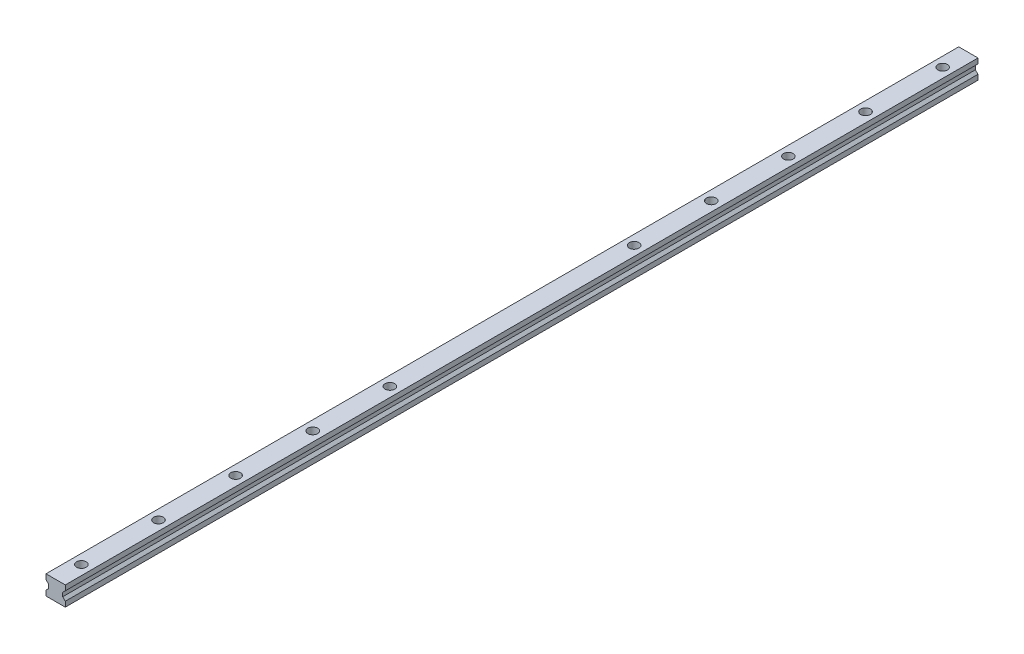
SolidWorks part; units mm, degrees
ref_plane "Front Plane" through (0, 0, 0) normal (0, 0, 1) x (1, 0, 0)
ref_plane "Top Plane" through (0, 0, 0) normal (0, 1, 0) x (1, 0, 0)
ref_plane "Right Plane" through (0, 0, 0) normal (1, 0, 0) x (0, 0, -1)
sketch "Sketch1" plane through (0, 0, 0) normal (0, 0, 1) x (1, 0, 0)
  line L0 (0, 17.31) -> (0, -6.39) construction
  line L1 (-7.5, 0) -> (7.5, 0)
  line L2 (7.5, 0) -> (7.5, 4)
  line L3 (7.5, 4) -> (5.5, 6)
  line L4 (5.5, 6) -> (5.5, 9)
  line L5 (5.5, 9) -> (7.5, 11)
  line L6 (7.5, 11) -> (7.5, 15)
  line L7 (7.5, 15) -> (-7.5, 15)
  line L8 (-7.5, 11) -> (-7.5, 15)
  line L9 (-5.5, 9) -> (-7.5, 11)
  line L10 (-5.5, 6) -> (-5.5, 9)
  line L11 (-7.5, 4) -> (-5.5, 6)
  line L12 (-7.5, 0) -> (-7.5, 4)
  point P11 (0, 15)
  point P17 (0, 0)
  dimension "D1" = 7.5
  dimension "D2" = 15
  dimension "D3" = 4
  dimension "D4" = 4
  dimension "D5" = 45
  dimension "D6" = 45
  dimension "D7" = 3
extrude "Boss-Extrude1" add sketch "Sketch1" along normal blind 710
sketch "Sketch2" plane through (0, 15, 0) normal (0, 1, 0) x (1, 0, 0)
  line L0 (0, 9.6071) -> (0, -39.3975) construction
  circle A0 centre (0, -20) radius 3.75
  circle A1 centre (0, -80) radius 3.75
  circle A2 centre (0, -140) radius 3.75
  circle A3 centre (0, -200) radius 3.75
  circle A4 centre (0, -260) radius 3.75
  dimension "D1" = 7.5
  dimension "D2" = 20
  dimension "D3" = 5
extrude "Cut-Extrude1" cut sketch "Sketch2" against normal blind 5.3
sketch "Sketch3" plane through (0, 15, 0) normal (0, 1, 0) x (1, 0, 0)
  circle A0 centre (0, -20) radius 2.25
  circle A1 centre (0, -80) radius 2.25
  circle A2 centre (0, -140) radius 2.25
  circle A3 centre (0, -200) radius 2.25
  circle A4 centre (0, -260) radius 2.25
  dimension "D1" = 4.5
  dimension "D2" = 5
extrude "Cut-Extrude2" cut sketch "Sketch3" against normal through all
ref_plane "基准面1" through (0, 0, 355) normal (0, 0, 1) x (1, 0, 0)
mirror "镜向1" about plane through (0, 0, 355) normal (0, 0, 1) of "Cut-Extrude1"
